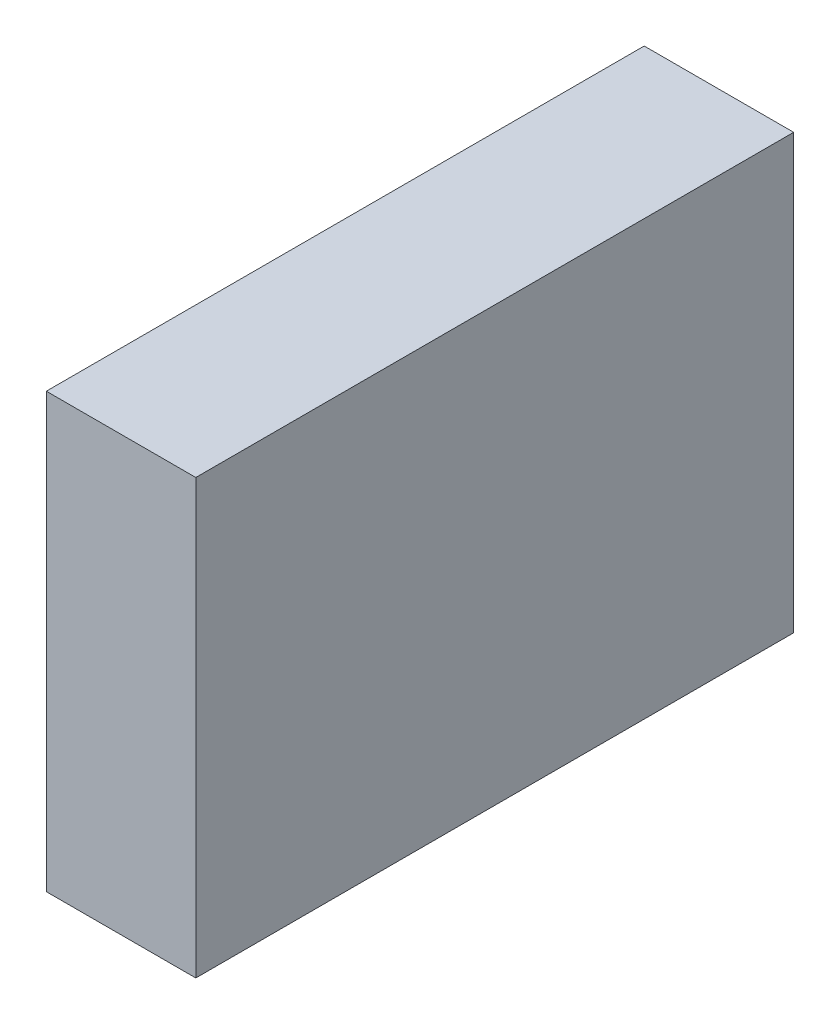
SolidWorks part; units mm, degrees
ref_plane "Front Plane" through (0, 0, 0) normal (0, 0, 1) x (1, 0, 0)
ref_plane "Top Plane" through (0, 0, 0) normal (0, 1, 0) x (1, 0, 0)
ref_plane "Right Plane" through (0, 0, 0) normal (1, 0, 0) x (0, 0, -1)
sketch "Sketch1" plane through (0, 0, 0) normal (1, 0, 0) x (0, 0, -1)
  line L1 (0, 0) -> (40, 0)
  line L2 (0, 0) -> (0, 29)
  line L3 (0, 29) -> (40, 29)
  line L4 (40, 0) -> (40, 29)
extrude "Boss-Extrude1" add sketch "Sketch1" against normal blind 10
